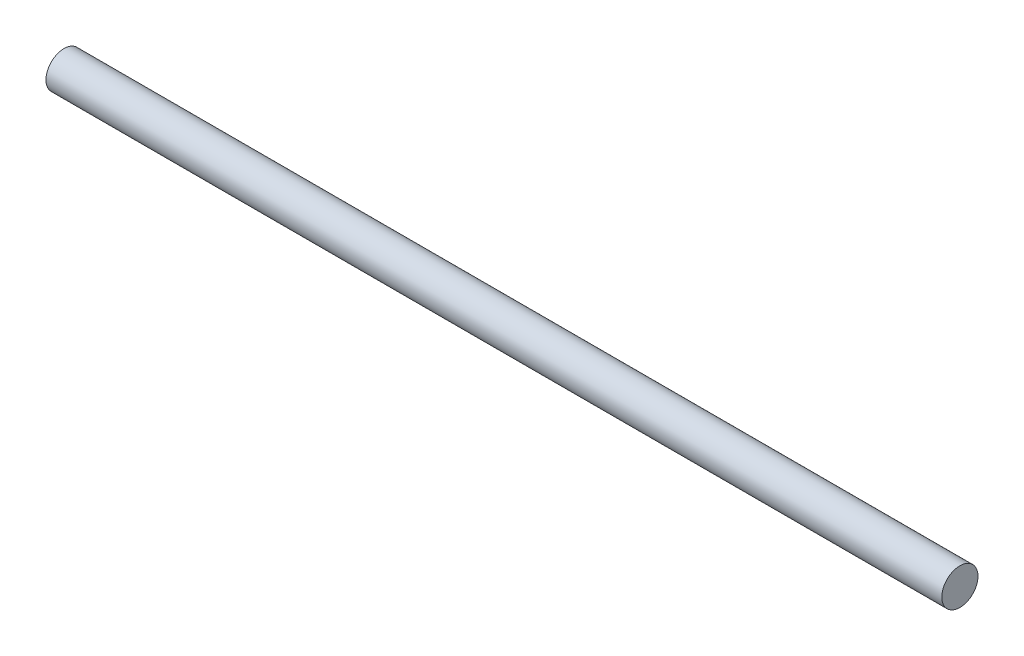
SolidWorks part; units mm, degrees
ref_plane "Front Plane" through (0, 0, 0) normal (0, 0, 1) x (1, 0, 0)
ref_plane "Top Plane" through (0, 0, 0) normal (0, 1, 0) x (1, 0, 0)
ref_plane "Right Plane" through (0, 0, 0) normal (1, 0, 0) x (0, 0, -1)
sketch "Sketch1" plane through (0, 0, 0) normal (1, 0, 0) x (0, 0, -1)
  circle A0 centre (0, 0) radius 6.35
  dimension "D1" = 12.7
extrude "Boss-Extrude1" add sketch "Sketch1" along normal blind 314.325
